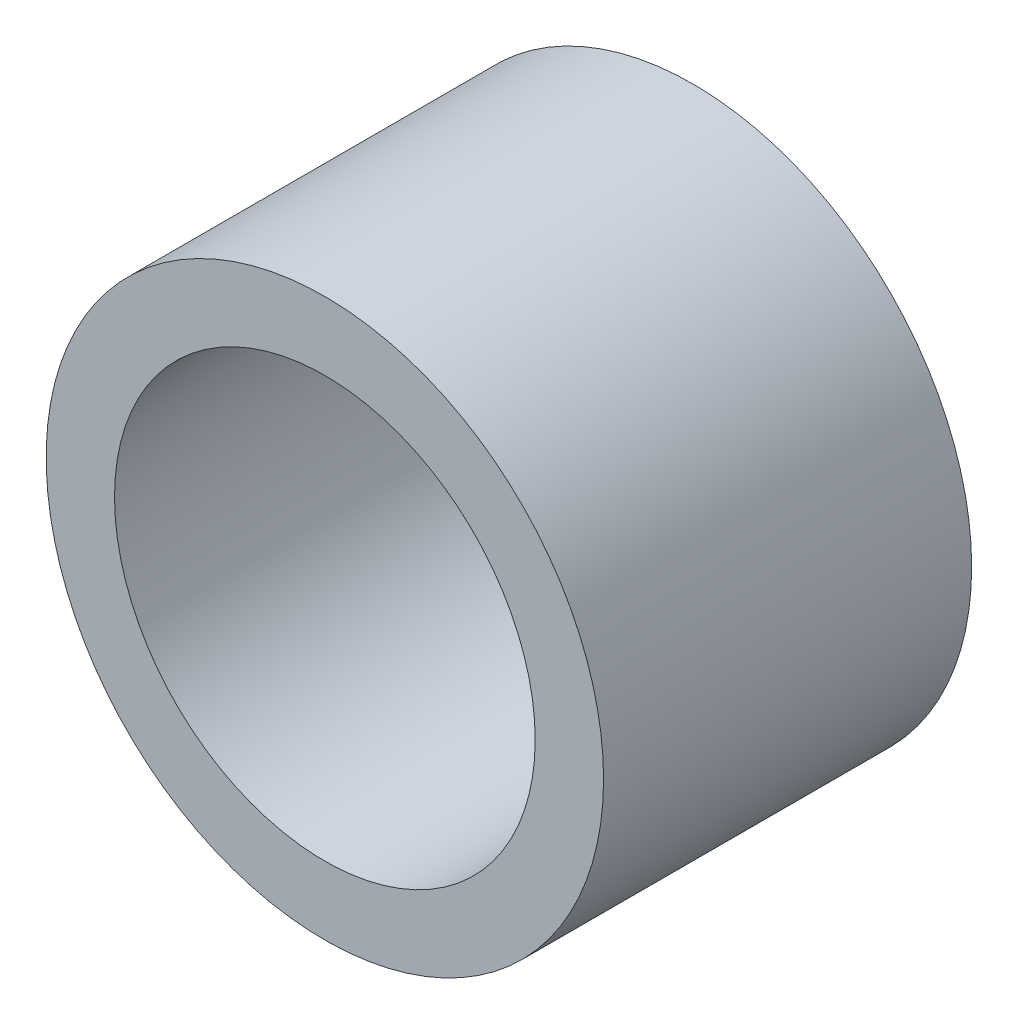
SolidWorks part; units mm, degrees
ref_plane "Alzado" through (0, 0, 0) normal (0, 0, 1) x (1, 0, 0)
ref_plane "Planta" through (0, 0, 0) normal (0, 1, 0) x (1, 0, 0)
ref_plane "Vista lateral" through (0, 0, 0) normal (1, 0, 0) x (0, 0, -1)
sketch "Croquis1" plane through (0, 0, 0) normal (0, 0, 1) x (1, 0, 0)
  circle A0 centre (0, 0) radius 5.3
  circle A1 centre (0, 0) radius 4
extrude "Saliente-Extruir1" add sketch "Croquis1" along normal blind 7
